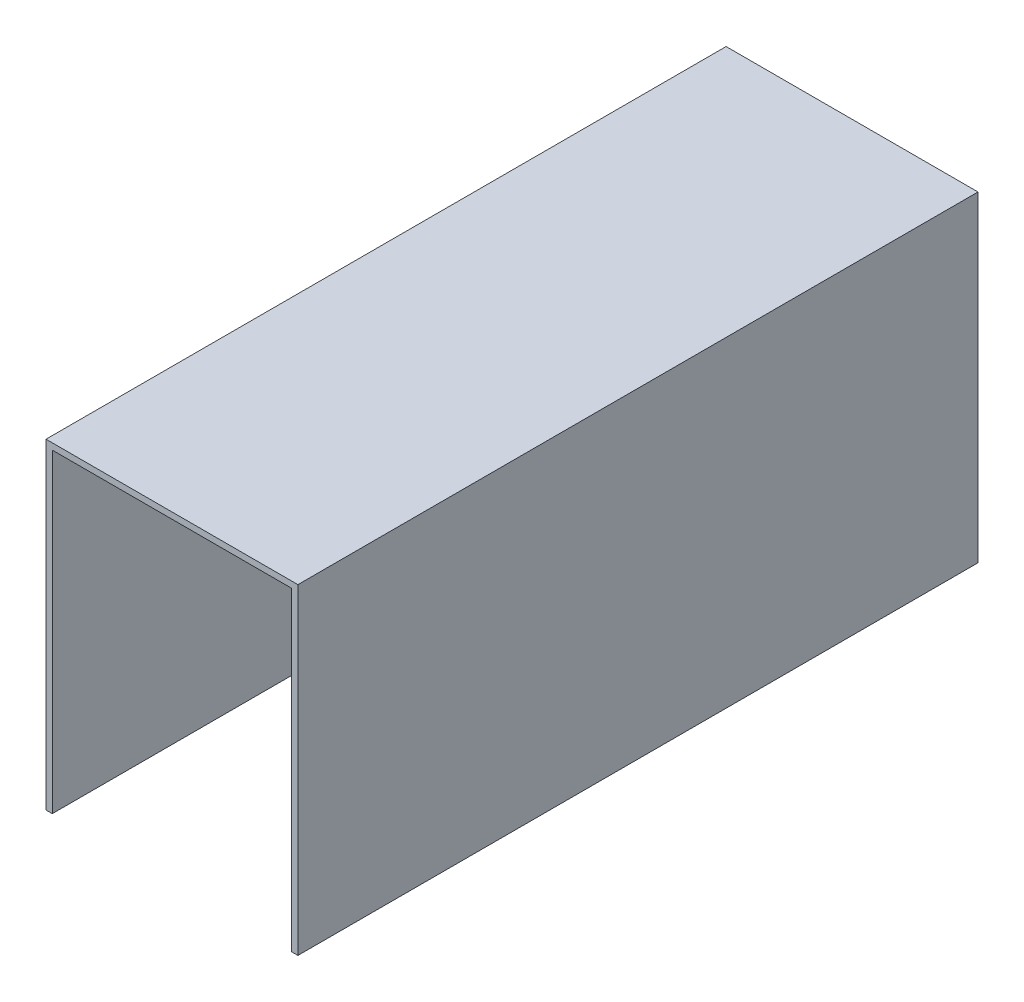
SolidWorks part; units mm, degrees
ref_plane "Plano frontal" through (0, 0, 0) normal (0, 0, 1) x (1, 0, 0)
ref_plane "Plano superior" through (0, 0, 0) normal (0, 1, 0) x (1, 0, 0)
ref_plane "Plano direito" through (0, 0, 0) normal (1, 0, 0) x (0, 0, -1)
sketch "Esboço1" plane through (0, 0, 0) normal (0, 0, 1) x (1, 0, 0)
  line L0 (-7.3363, 0) -> (-7.3363, 50)
  line L1 (-7.3363, 50) -> (30.6637, 50)
  line L2 (30.6637, 50) -> (30.6637, 0)
  line L3 (30.6637, 0) -> (31.6637, 0)
  line L4 (31.6637, 0) -> (31.6637, 51)
  line L5 (31.6637, 51) -> (-8.3363, 51)
  line L6 (-8.3363, 51) -> (-8.3363, 0)
  line L7 (-8.3363, 0) -> (-7.3363, 0)
  dimension "D1" = 1
  dimension "D2" = 1
  dimension "D3" = 1
  dimension "D4" = 38
  dimension "D5" = 50
extrude "Ressalto-extrusão1" add sketch "Esboço1" along normal blind 108
